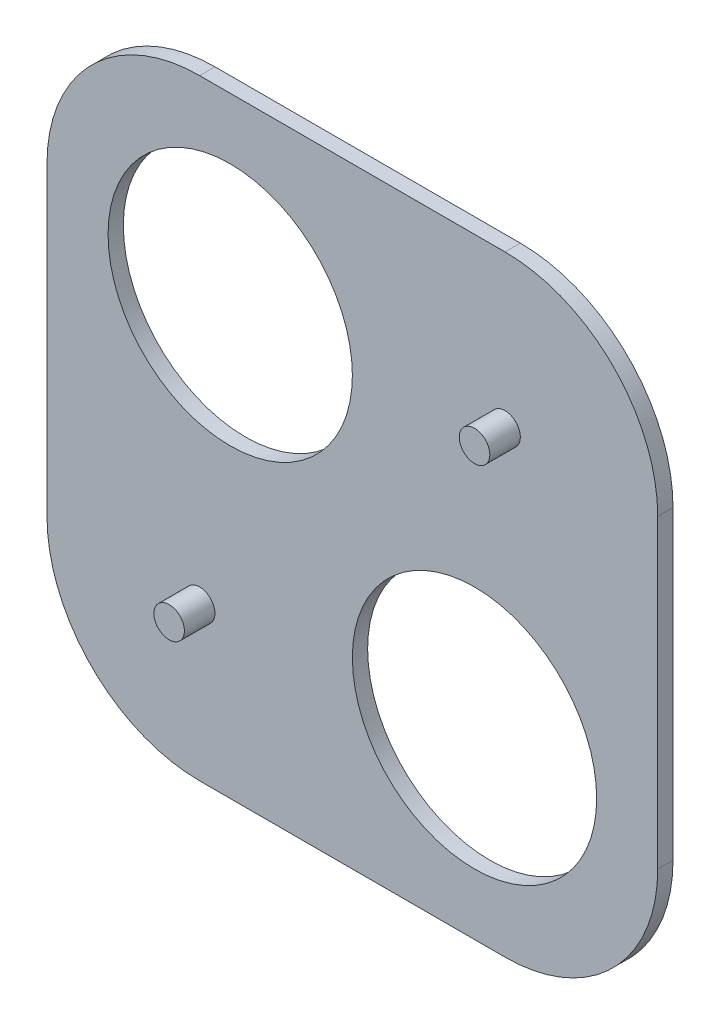
SolidWorks part; units mm, degrees
ref_plane "Front Plane" through (0, 0, 0) normal (0, 0, 1) x (1, 0, 0)
ref_plane "Top Plane" through (0, 0, 0) normal (0, 1, 0) x (1, 0, 0)
ref_plane "Right Plane" through (0, 0, 0) normal (1, 0, 0) x (0, 0, -1)
sketch "Sketch1" plane through (0, 0, 0) normal (0, 0, 1) x (1, 0, 0)
  line L1 (-500, 1000) -> (500, 1000)
  line L2 (-1000, 500) -> (-1000, -500)
  line L3 (-500, -1000) -> (500, -1000)
  line L4 (1000, 500) -> (1000, -500)
  line L5 (-1000, 1000) -> (1000, -1000) construction
  line L6 (-1000, -1000) -> (1000, 1000) construction
  arc A0 (-1000, -500) -> (-500, -1000) centre (-500, -500) ccw
  arc A1 (1000, -500) -> (500, -1000) centre (500, -500) cw
  arc A2 (500, 1000) -> (1000, 500) centre (500, 500) cw
  arc A3 (-1000, 500) -> (-500, 1000) centre (-500, 500) cw
  point P0 (0, 0)
  dimension "D3" = 500
  dimension "D4" = 500
  dimension "D5" = 500
  dimension "D6" = 500
  dimension "D1" = 2000
  dimension "D2" = 2000
extrude "Boss-Extrude1" add sketch "Sketch1" along normal blind 50
sketch "Sketch2" plane through (0, 0, 50) normal (0, 0, 1) x (1, 0, 0)
  line L0 (0, 1314.3016) -> (0, -1366.0272) construction
  line L1 (-1464.0216, 0) -> (1498.4471, 0) construction
  line L2 (-500, -1366.0272) -> (-500, 0) construction
  line L3 (-1464.0216, -500) -> (0, -500) construction
  line L4 (500, 0) -> (500, 1314.3016) construction
  line L5 (0, 500) -> (1498.4471, 500) construction
  circle A0 centre (-500, -500) radius 50
  circle A1 centre (500, 500) radius 50
  dimension "D5" = 100
  dimension "D6" = 100
  dimension "D1" = 500
  dimension "D2" = 500
  dimension "D3" = 500
  dimension "D4" = 500
extrude "Boss-Extrude2" add sketch "Sketch2" along normal blind 100
sketch "Sketch3" plane through (0, 0, 50) normal (0, 0, 1) x (1, 0, 0)
  circle A0 centre (400, -400) radius 400
  circle A1 centre (-400, 400) radius 400
  dimension "D3" = 800
  dimension "D6" = 800
  dimension "D1" = 400
  dimension "D2" = 400
  dimension "D4" = 400
  dimension "D5" = 400
extrude "Cut-Extrude1" cut sketch "Sketch3" against normal blind 100
